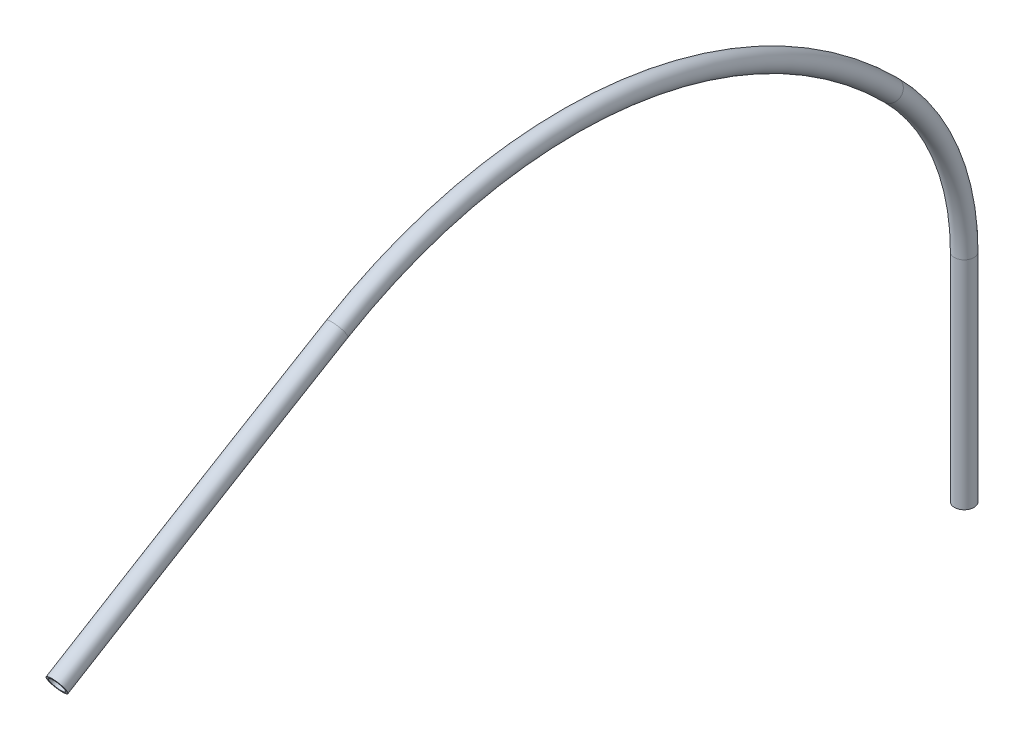
SolidWorks part; units mm, degrees
ref_plane "Alzado" through (0, 0, 0) normal (0, 0, 1) x (1, 0, 0)
ref_plane "Planta" through (0, 0, 0) normal (0, 1, 0) x (1, 0, 0)
ref_plane "Vista lateral" through (0, 0, 0) normal (1, 0, 0) x (0, 0, -1)
sketch "Croquis5" plane through (0, 0, 0) normal (1, 0, 0) x (0, 0, -1)
  line L0 (-12, 40) -> (-12, 150.7554)
  arc A0 (-12, 150.7554) -> (-49.2628, 241.0374) centre (-140.0011, 150.7554) ccw
  arc A1 (-49.2628, 241.0374) -> (-332.9206, 277.0647) centre (-214.2261, 76.9036) ccw
  arc A2 (-332.9206, 277.0647) -> (-476.2262, 190.8469) centre (6364.2347, -11016.7175) ccw
  dimension "D1" = 40
ref_plane "Plano1" through (0, 40, 12) normal (0, 1, 0) x (-1, 0, 0)
sketch "Croquis7" plane through (0, 40, 12) normal (0, 1, 0) x (-1, 0, 0)
  circle A0 centre (0, 0) radius 5
  dimension "D1" = 10
sweep "Barrer1" add profiles "Croquis7" path "Croquis5"
shell "Vaciado2" thickness 1
